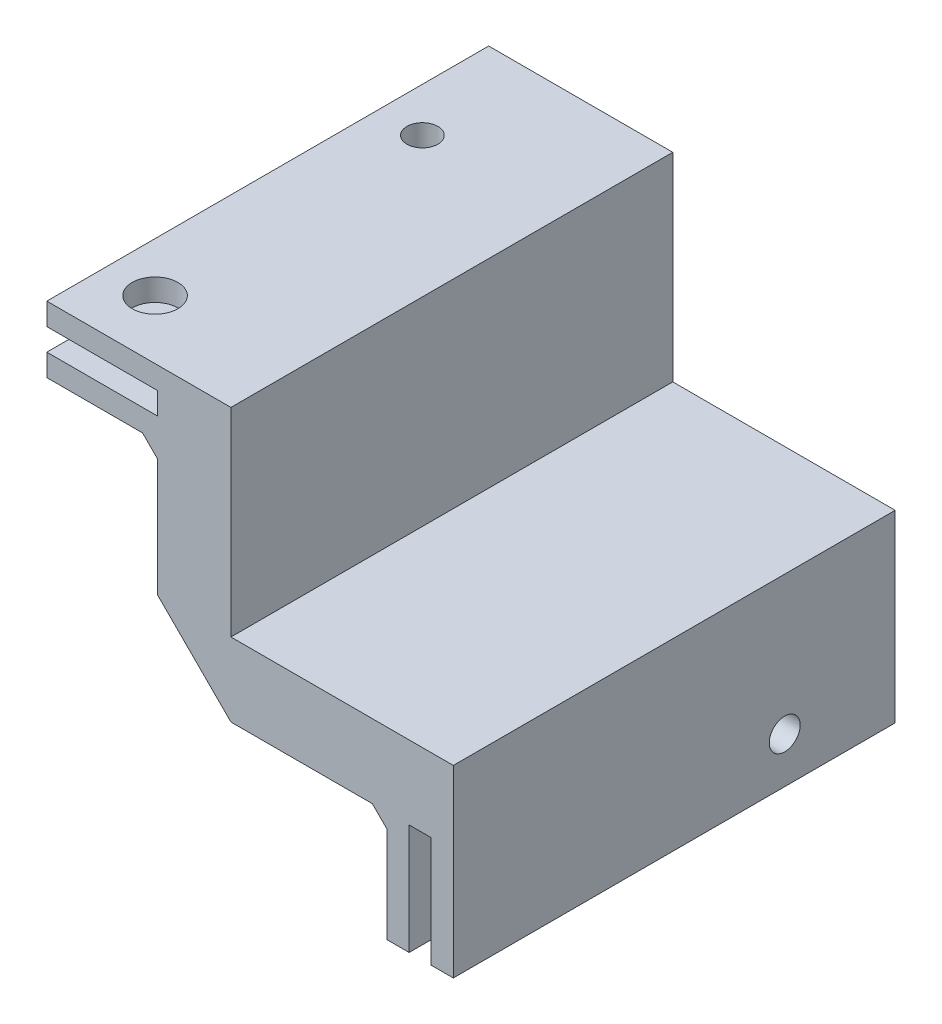
SolidWorks part; units mm, degrees
material "ABS"
ref_plane "Płaszczyzna przednia" through (0, 0, 0) normal (0, 0, 1) x (1, 0, 0)
ref_plane "Płaszczyzna górna" through (0, 0, 0) normal (0, 1, 0) x (1, 0, 0)
ref_plane "Płaszczyzna prawa" through (0, 0, 0) normal (1, 0, 0) x (0, 0, -1)
sketch "Szkic1" plane through (0, 0, 0) normal (0, 0, 1) x (1, 0, 0)
  line L0 (0, 0) -> (-3, 0)
  line L1 (-3, 0) -> (-3, 15)
  line L2 (-3, 15) -> (-6, 15)
  line L3 (-6, 15) -> (-6, 0)
  line L4 (-6, 0) -> (-9, 0)
  line L5 (-9, 0) -> (-9, 15)
  line L6 (0, 0) -> (0, 25)
  line L7 (0, 25) -> (-30.2, 25)
  line L8 (-9, 15) -> (-30.2, 15)
  line L9 (-30.2, 25) -> (-30.2, 52)
  line L10 (-30.2, 52) -> (-55.2, 52)
  line L11 (-55.2, 52) -> (-55.2, 49)
  line L12 (-55.2, 49) -> (-40.2, 49)
  line L13 (-40.2, 49) -> (-40.2, 46)
  line L14 (-40.2, 46) -> (-55.2, 46)
  line L15 (-55.2, 46) -> (-55.2, 43)
  line L16 (-55.2, 43) -> (-40.2, 43)
  line L17 (-40.2, 43) -> (-40.2, 25)
  line L18 (-40.2, 25) -> (-30.2, 15)
  dimension "D1" = 3
  dimension "D2" = 3
  dimension "D3" = 3
  dimension "D4" = 15
  dimension "D5" = 25
  dimension "D6" = 30.2
  dimension "D7" = 21.2
  dimension "D8" = 3
  dimension "D9" = 3
  dimension "D10" = 3
  dimension "D11" = 15
  dimension "D12" = 10
  dimension "D13" = 27
  dimension "D14" = 18
extrude "Dodanie-wyciągnięcie1" add sketch "Szkic1" along normal blind 60
chamfer "Sfazowanie1" distance 2 angle 45 2 edges at (-9, 15, 30) (-40.2, 43, 30)
sketch "Szkic2" plane through (0, 43, 0) normal (0, -1, 0) x (1, 0, 0)
  line L0 (-40.2, 60) -> (-40.2, 0) construction
  line L1 (-55.2, 60) -> (-42.2, 60) construction
  circle A0 centre (-48.5, 52) radius 3.1
  dimension "D1" = 6.2
  dimension "D3" = 8
  dimension "D2" = 8.3
extrude "Wytnij-wyciągnięcie1" cut sketch "Szkic2" against normal blind 10
sketch "Szkic3" plane through (0, 43, 0) normal (0, -1, 0) x (1, 0, 0)
  line L0 (-40.2, 60) -> (-40.2, 0) construction
  line L1 (-55.2, 0) -> (-42.2, 0) construction
  circle A0 centre (-49.2, 15) radius 2.1
  dimension "D1" = 4.2
  dimension "D2" = 9
  dimension "D3" = 15
extrude "Wytnij-wyciągnięcie2" cut sketch "Szkic3" against normal blind 10
sketch "Szkic4" plane through (-9, 0, 0) normal (-1, 0, 0) x (0, 0, 1)
  line L0 (0, 15) -> (60, 15) construction
  line L1 (0, 13) -> (0, 0) construction
  circle A0 centre (15, 6.2) radius 2.1
  point P6 (0, 6.5)
  dimension "D1" = 4.2
  dimension "D2" = 8.8
  dimension "D3" = 15
extrude "Wytnij-wyciągnięcie3" cut sketch "Szkic4" against normal blind 10
